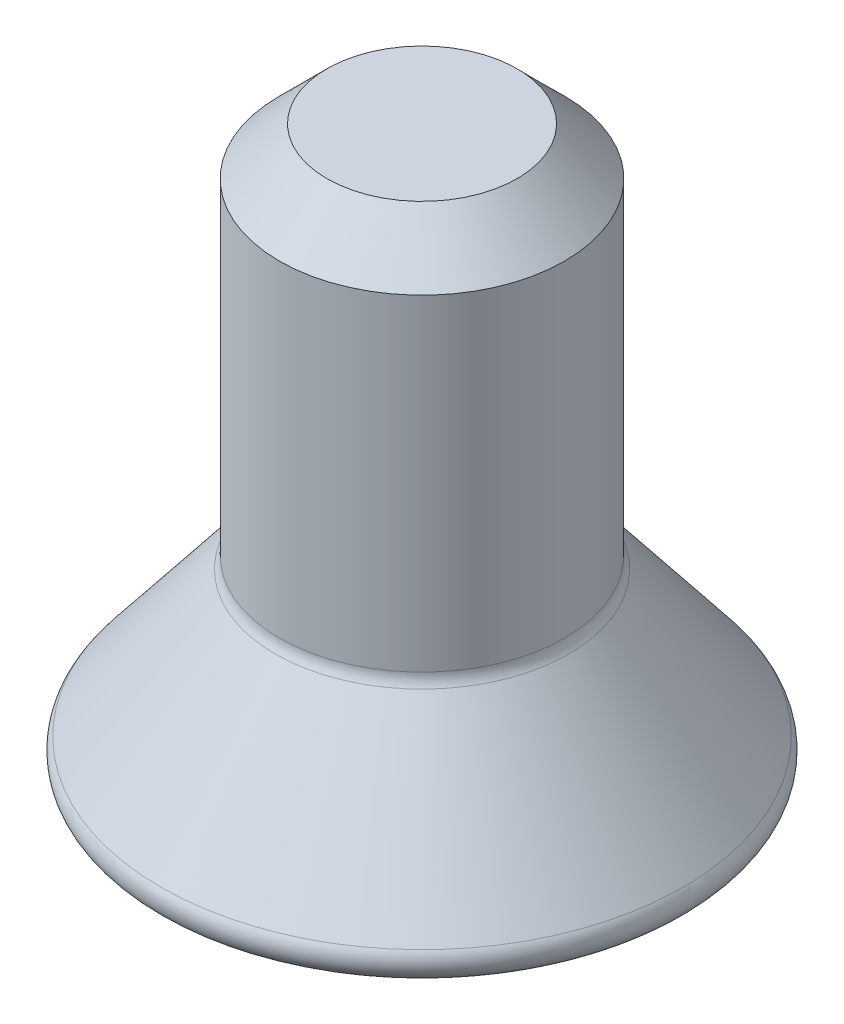
SolidWorks part; units mm, degrees
ref_plane "前视基准面" through (0, 0, 0) normal (0, 0, 1) x (1, 0, 0)
ref_plane "上视基准面" through (0, 0, 0) normal (0, 1, 0) x (1, 0, 0)
ref_plane "右视基准面" through (0, 0, 0) normal (1, 0, 0) x (0, 0, -1)
sketch "草图1" plane through (0, 0, 0) normal (0, 0, 1) x (1, 0, 0)
  line L0 (0, 3.3103) -> (0, -3.8641) construction
  line L1 (0, 1.9) -> (1.5, 1.9)
  line L2 (1.5, 1.9) -> (3, 0)
  line L3 (3, 0) -> (0, 0)
  line L4 (0, 1.9) -> (0, 0)
  dimension "D1" = 1.5
  dimension "D2" = 3
  dimension "D3" = 1.9
revolve "旋转2" add sketch "草图1" angle 360 about L0
sketch "草图2" plane through (0, 1.9, 0) normal (0, 1, 0) x (1, 0, 0)
  circle A0 centre (0, 0) radius 1.5
extrude "凸台-拉伸1" add sketch "草图2" along normal blind 4
sketch "草图3" plane through (0, 0, 0) normal (0, -1, 0) x (1, 0, 0)
  line L1 (0, 1.1547) -> (-1, 0.5774)
  line L2 (-1, 0.5774) -> (-1, -0.5774)
  line L3 (-1, -0.5774) -> (0, -1.1547)
  line L4 (0, -1.1547) -> (1, -0.5774)
  line L5 (1, -0.5774) -> (1, 0.5774)
  line L6 (1, 0.5774) -> (0, 1.1547)
  circle A1 centre (0, 0) radius 1 construction
  dimension "D1" = 2
extrude "切除-拉伸1" cut sketch "草图3" against normal blind 1
chamfer "倒角1" distance 0.5 angle 45 1 edges at (0, 5.9, 1.5)
fillet "圆角1" radius 0.2 2 edges at (0, 1.9, 1.5) (0, 0, 3)
